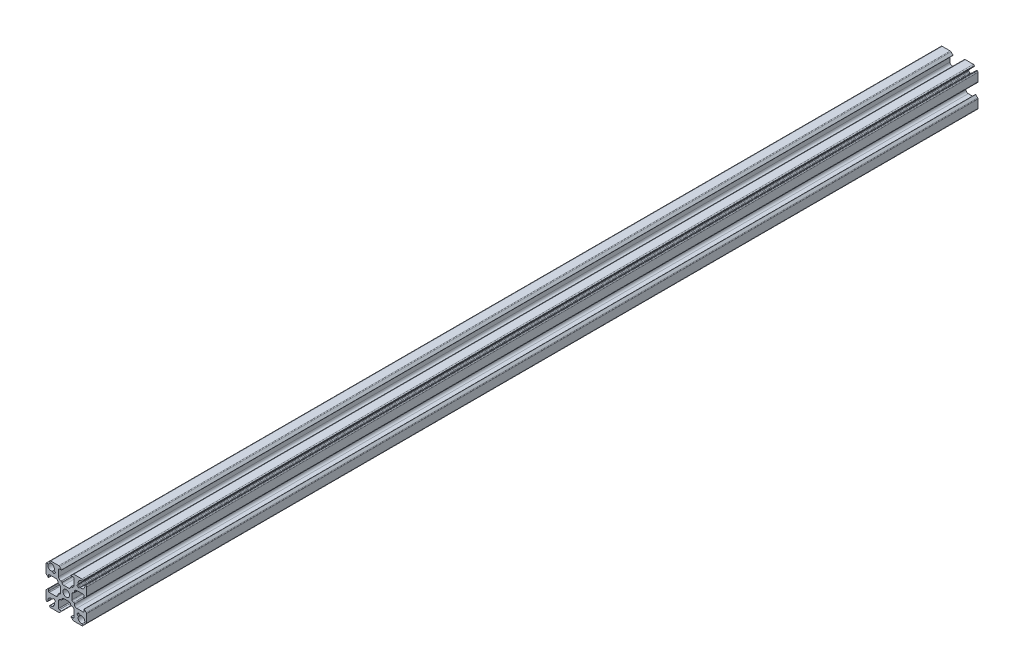
SolidWorks part; units mm, degrees
ref_plane "Front Plane" through (0, 0, 0) normal (0, 0, 1) x (1, 0, 0)
ref_plane "Top Plane" through (0, 0, 0) normal (0, 1, 0) x (1, 0, 0)
ref_plane "Right Plane" through (0, 0, 0) normal (1, 0, 0) x (0, 0, -1)
sketch "Sketch1" plane through (0, 0, 0) normal (0, 0, 1) x (1, 0, 0)
  line L0 (6.9856, 8.117) -> (7.4885, 8.6199)
  line L1 (9.7594, 12.7) -> (4.7107, 12.7)
  line L2 (4.1803, 12.4803) -> (2.9707, 11.2707)
  line L3 (3.0414, 11.1) -> (4.325, 11.1)
  line L4 (4.825, 10.6) -> (4.825, 6.6)
  line L5 (3.325, 5.1) -> (3.15, 5.1)
  line L6 (1.65, 3.6) -> (-1.65, 3.6)
  line L7 (-3.15, 5.1) -> (-3.325, 5.1)
  line L8 (-4.825, 6.6) -> (-4.825, 10.6)
  line L9 (-4.325, 11.1) -> (-3.0414, 11.1)
  line L10 (-2.9707, 11.2707) -> (-4.1803, 12.4803)
  line L11 (-4.7107, 12.7) -> (-9.7594, 12.7)
  line L12 (-7.4885, 8.6199) -> (-6.9856, 8.117)
  line L13 (-6.9856, 7.4099) -> (-7.4099, 6.9856)
  line L14 (-8.117, 6.9856) -> (-8.6199, 7.4885)
  line L15 (-12.7, 9.7594) -> (-12.7, 4.7107)
  line L16 (-12.4803, 4.1803) -> (-11.2707, 2.9707)
  line L17 (-11.1, 3.0414) -> (-11.1, 4.325)
  line L18 (-10.6, 4.825) -> (-6.6, 4.825)
  line L19 (-5.1, 3.325) -> (-5.1, 3.15)
  line L20 (-3.6, 1.65) -> (-3.6, -1.65)
  line L21 (-5.1, -3.15) -> (-5.1, -3.325)
  line L22 (-6.6, -4.825) -> (-10.6, -4.825)
  line L23 (-11.1, -4.325) -> (-11.1, -3.0414)
  line L24 (-11.2707, -2.9707) -> (-12.4803, -4.1803)
  line L25 (-12.7, -4.7107) -> (-12.7, -9.7594)
  line L26 (-8.6199, -7.4885) -> (-8.117, -6.9856)
  line L27 (-7.4099, -6.9856) -> (-6.9856, -7.4099)
  line L28 (-6.9856, -8.117) -> (-7.4885, -8.6199)
  line L29 (-9.7594, -12.7) -> (-4.7107, -12.7)
  line L30 (-4.1803, -12.4803) -> (-2.9707, -11.2707)
  line L31 (-3.0414, -11.1) -> (-4.325, -11.1)
  line L32 (-4.825, -10.6) -> (-4.825, -6.6)
  line L33 (-3.325, -5.1) -> (-3.15, -5.1)
  line L34 (-1.65, -3.6) -> (1.65, -3.6)
  line L35 (3.15, -5.1) -> (3.325, -5.1)
  line L36 (4.825, -6.6) -> (4.825, -10.6)
  line L37 (4.325, -11.1) -> (3.0414, -11.1)
  line L38 (2.9707, -11.2707) -> (4.1803, -12.4803)
  line L39 (4.7107, -12.7) -> (9.7594, -12.7)
  line L40 (7.4885, -8.6199) -> (6.9856, -8.117)
  line L41 (6.9856, -7.4099) -> (7.4099, -6.9856)
  line L42 (8.117, -6.9856) -> (8.6199, -7.4885)
  line L43 (12.7, -9.7594) -> (12.7, -4.7107)
  line L44 (12.4803, -4.1803) -> (11.2707, -2.9707)
  line L45 (11.1, -3.0414) -> (11.1, -4.325)
  line L46 (10.6, -4.825) -> (6.6, -4.825)
  line L47 (5.1, -3.325) -> (5.1, -3.15)
  line L48 (3.6, -1.65) -> (3.6, 1.65)
  line L49 (5.1, 3.15) -> (5.1, 3.325)
  line L50 (6.6, 4.825) -> (10.6, 4.825)
  line L51 (11.1, 4.325) -> (11.1, 3.0414)
  line L52 (11.2707, 2.9707) -> (12.4803, 4.1803)
  line L53 (12.7, 4.7107) -> (12.7, 9.7594)
  line L54 (8.6199, 7.4885) -> (8.117, 6.9856)
  line L55 (7.4099, 6.9856) -> (6.9856, 7.4099)
  circle A0 centre (0, 0) radius 2.08
  arc A1 (6.9856, 8.117) -> (6.9856, 7.4099) centre (7.3392, 7.7635) ccw
  arc A2 (7.4885, 8.6199) -> (7.5492, 8.8748) centre (7.3118, 8.7967) ccw
  arc A3 (9.8933, 11.5721) -> (7.5492, 8.8748) centre (9.525, 9.525) ccw
  arc A4 (9.8933, 11.5721) -> (10.4266, 12.2927) centre (9.9818, 12.0642) ccw
  arc A5 (10.4266, 12.2927) -> (9.7594, 12.7) centre (9.7594, 11.95) ccw
  arc A6 (4.7107, 12.7) -> (4.1803, 12.4803) centre (4.7107, 11.95) ccw
  arc A7 (2.9707, 11.2707) -> (3.0414, 11.1) centre (3.0414, 11.2) ccw
  arc A8 (4.825, 10.6) -> (4.325, 11.1) centre (4.325, 10.6) ccw
  arc A9 (3.325, 5.1) -> (4.825, 6.6) centre (3.325, 6.6) ccw
  arc A10 (3.15, 5.1) -> (2.65, 4.6) centre (3.15, 4.6) ccw
  arc A11 (1.65, 3.6) -> (2.65, 4.6) centre (1.65, 4.6) ccw
  arc A12 (-2.65, 4.6) -> (-1.65, 3.6) centre (-1.65, 4.6) ccw
  arc A13 (-2.65, 4.6) -> (-3.15, 5.1) centre (-3.15, 4.6) ccw
  arc A14 (-4.825, 6.6) -> (-3.325, 5.1) centre (-3.325, 6.6) ccw
  arc A15 (-4.325, 11.1) -> (-4.825, 10.6) centre (-4.325, 10.6) ccw
  arc A16 (-3.0414, 11.1) -> (-2.9707, 11.2707) centre (-3.0414, 11.2) ccw
  arc A17 (-4.1803, 12.4803) -> (-4.7107, 12.7) centre (-4.7107, 11.95) ccw
  arc A18 (-9.7594, 12.7) -> (-10.4266, 12.2927) centre (-9.7594, 11.95) ccw
  arc A19 (-10.4266, 12.2927) -> (-9.8933, 11.5721) centre (-9.9818, 12.0642) ccw
  arc A20 (-7.5492, 8.8748) -> (-9.8933, 11.5721) centre (-9.525, 9.525) ccw
  arc A21 (-7.5492, 8.8748) -> (-7.4885, 8.6199) centre (-7.3118, 8.7967) ccw
  arc A22 (-6.9856, 7.4099) -> (-6.9856, 8.117) centre (-7.3392, 7.7635) ccw
  arc A23 (-8.117, 6.9856) -> (-7.4099, 6.9856) centre (-7.7635, 7.3392) ccw
  arc A24 (-8.6199, 7.4885) -> (-8.8748, 7.5492) centre (-8.7967, 7.3118) ccw
  arc A25 (-11.5721, 9.8933) -> (-8.8748, 7.5492) centre (-9.525, 9.525) ccw
  arc A26 (-11.5721, 9.8933) -> (-12.2927, 10.4266) centre (-12.0642, 9.9818) ccw
  arc A27 (-12.2927, 10.4266) -> (-12.7, 9.7594) centre (-11.95, 9.7594) ccw
  arc A28 (-12.7, 4.7107) -> (-12.4803, 4.1803) centre (-11.95, 4.7107) ccw
  arc A29 (-11.2707, 2.9707) -> (-11.1, 3.0414) centre (-11.2, 3.0414) ccw
  arc A30 (-10.6, 4.825) -> (-11.1, 4.325) centre (-10.6, 4.325) ccw
  arc A31 (-5.1, 3.325) -> (-6.6, 4.825) centre (-6.6, 3.325) ccw
  arc A32 (-5.1, 3.15) -> (-4.6, 2.65) centre (-4.6, 3.15) ccw
  arc A33 (-3.6, 1.65) -> (-4.6, 2.65) centre (-4.6, 1.65) ccw
  arc A34 (-4.6, -2.65) -> (-3.6, -1.65) centre (-4.6, -1.65) ccw
  arc A35 (-4.6, -2.65) -> (-5.1, -3.15) centre (-4.6, -3.15) ccw
  arc A36 (-6.6, -4.825) -> (-5.1, -3.325) centre (-6.6, -3.325) ccw
  arc A37 (-11.1, -4.325) -> (-10.6, -4.825) centre (-10.6, -4.325) ccw
  arc A38 (-11.1, -3.0414) -> (-11.2707, -2.9707) centre (-11.2, -3.0414) ccw
  arc A39 (-12.4803, -4.1803) -> (-12.7, -4.7107) centre (-11.95, -4.7107) ccw
  arc A40 (-12.7, -9.7594) -> (-12.2927, -10.4266) centre (-11.95, -9.7594) ccw
  arc A41 (-12.2927, -10.4266) -> (-11.5721, -9.8933) centre (-12.0642, -9.9818) ccw
  arc A42 (-8.8748, -7.5492) -> (-11.5721, -9.8933) centre (-9.525, -9.525) ccw
  arc A43 (-8.8748, -7.5492) -> (-8.6199, -7.4885) centre (-8.7967, -7.3118) ccw
  arc A44 (-7.4099, -6.9856) -> (-8.117, -6.9856) centre (-7.7635, -7.3392) ccw
  arc A45 (-6.9856, -8.117) -> (-6.9856, -7.4099) centre (-7.3392, -7.7635) ccw
  arc A46 (-7.4885, -8.6199) -> (-7.5492, -8.8748) centre (-7.3118, -8.7967) ccw
  arc A47 (-9.8933, -11.5721) -> (-7.5492, -8.8748) centre (-9.525, -9.525) ccw
  arc A48 (-9.8933, -11.5721) -> (-10.4266, -12.2927) centre (-9.9818, -12.0642) ccw
  arc A49 (-10.4266, -12.2927) -> (-9.7594, -12.7) centre (-9.7594, -11.95) ccw
  arc A50 (-4.7107, -12.7) -> (-4.1803, -12.4803) centre (-4.7107, -11.95) ccw
  arc A51 (-2.9707, -11.2707) -> (-3.0414, -11.1) centre (-3.0414, -11.2) ccw
  arc A52 (-4.825, -10.6) -> (-4.325, -11.1) centre (-4.325, -10.6) ccw
  arc A53 (-3.325, -5.1) -> (-4.825, -6.6) centre (-3.325, -6.6) ccw
  arc A54 (-3.15, -5.1) -> (-2.65, -4.6) centre (-3.15, -4.6) ccw
  arc A55 (-1.65, -3.6) -> (-2.65, -4.6) centre (-1.65, -4.6) ccw
  arc A56 (2.65, -4.6) -> (1.65, -3.6) centre (1.65, -4.6) ccw
  arc A57 (2.65, -4.6) -> (3.15, -5.1) centre (3.15, -4.6) ccw
  arc A58 (4.825, -6.6) -> (3.325, -5.1) centre (3.325, -6.6) ccw
  arc A59 (4.325, -11.1) -> (4.825, -10.6) centre (4.325, -10.6) ccw
  arc A60 (3.0414, -11.1) -> (2.9707, -11.2707) centre (3.0414, -11.2) ccw
  arc A61 (4.1803, -12.4803) -> (4.7107, -12.7) centre (4.7107, -11.95) ccw
  arc A62 (9.7594, -12.7) -> (10.4266, -12.2927) centre (9.7594, -11.95) ccw
  arc A63 (10.4266, -12.2927) -> (9.8933, -11.5721) centre (9.9818, -12.0642) ccw
  arc A64 (7.5492, -8.8748) -> (9.8933, -11.5721) centre (9.525, -9.525) ccw
  arc A65 (7.5492, -8.8748) -> (7.4885, -8.6199) centre (7.3118, -8.7967) ccw
  arc A66 (6.9856, -7.4099) -> (6.9856, -8.117) centre (7.3392, -7.7635) ccw
  arc A67 (8.117, -6.9856) -> (7.4099, -6.9856) centre (7.7635, -7.3392) ccw
  arc A68 (8.6199, -7.4885) -> (8.8748, -7.5492) centre (8.7967, -7.3118) ccw
  arc A69 (11.5721, -9.8933) -> (8.8748, -7.5492) centre (9.525, -9.525) ccw
  arc A70 (11.5721, -9.8933) -> (12.2927, -10.4266) centre (12.0642, -9.9818) ccw
  arc A71 (12.2927, -10.4266) -> (12.7, -9.7594) centre (11.95, -9.7594) ccw
  arc A72 (12.7, -4.7107) -> (12.4803, -4.1803) centre (11.95, -4.7107) ccw
  arc A73 (11.2707, -2.9707) -> (11.1, -3.0414) centre (11.2, -3.0414) ccw
  arc A74 (10.6, -4.825) -> (11.1, -4.325) centre (10.6, -4.325) ccw
  arc A75 (5.1, -3.325) -> (6.6, -4.825) centre (6.6, -3.325) ccw
  arc A76 (5.1, -3.15) -> (4.6, -2.65) centre (4.6, -3.15) ccw
  arc A77 (3.6, -1.65) -> (4.6, -2.65) centre (4.6, -1.65) ccw
  arc A78 (4.6, 2.65) -> (3.6, 1.65) centre (4.6, 1.65) ccw
  arc A79 (4.6, 2.65) -> (5.1, 3.15) centre (4.6, 3.15) ccw
  arc A80 (6.6, 4.825) -> (5.1, 3.325) centre (6.6, 3.325) ccw
  arc A81 (11.1, 4.325) -> (10.6, 4.825) centre (10.6, 4.325) ccw
  arc A82 (11.1, 3.0414) -> (11.2707, 2.9707) centre (11.2, 3.0414) ccw
  arc A83 (12.4803, 4.1803) -> (12.7, 4.7107) centre (11.95, 4.7107) ccw
  arc A84 (12.7, 9.7594) -> (12.2927, 10.4266) centre (11.95, 9.7594) ccw
  arc A85 (12.2927, 10.4266) -> (11.5721, 9.8933) centre (12.0642, 9.9818) ccw
  arc A86 (8.8748, 7.5492) -> (11.5721, 9.8933) centre (9.525, 9.525) ccw
  arc A87 (8.8748, 7.5492) -> (8.6199, 7.4885) centre (8.7967, 7.3118) ccw
  arc A88 (7.4099, 6.9856) -> (8.117, 6.9856) centre (7.7635, 7.3392) ccw
extrude "Boss-Extrude1" add sketch "Sketch1" along normal blind 558.8
